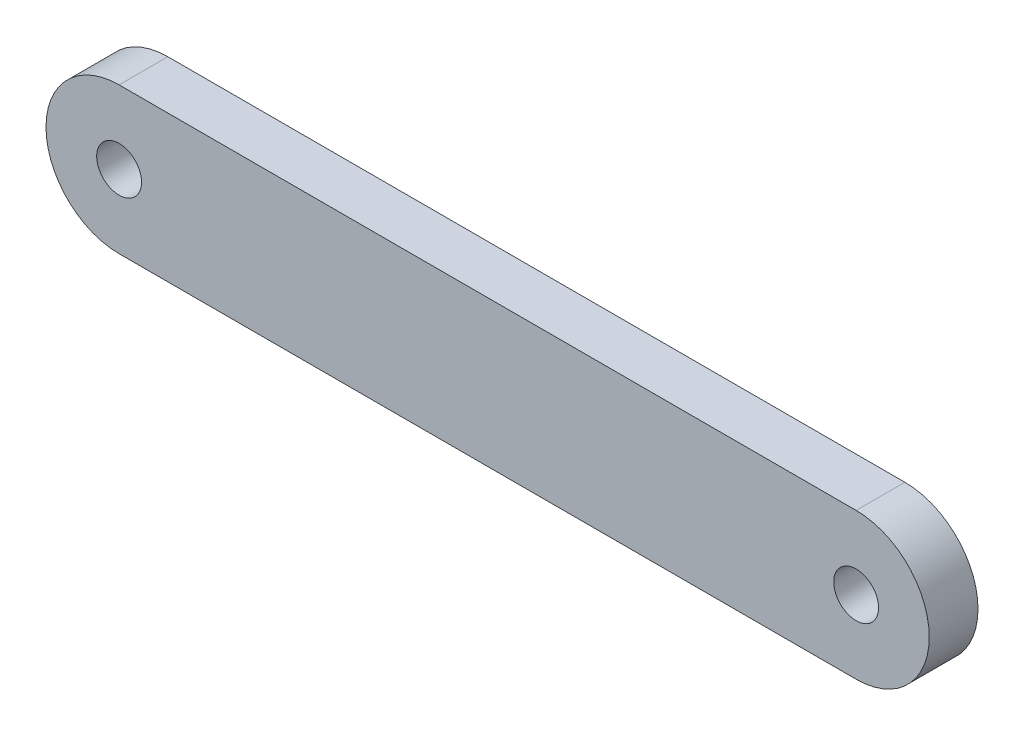
SolidWorks part; units mm, degrees
ref_plane "前视基准面" through (0, 0, 0) normal (0, 0, 1) x (1, 0, 0)
ref_plane "上视基准面" through (0, 0, 0) normal (0, 1, 0) x (1, 0, 0)
ref_plane "右视基准面" through (0, 0, 0) normal (1, 0, 0) x (0, 0, -1)
other "Configuration Table"
sketch "草图1" plane through (0, 0, 0) normal (0, 0, 1) x (1, 0, 0)
  line L1 (-37.8, 7.5) -> (37.8, 7.5)
  line L3 (-37.8, -7.5) -> (37.8, -7.5)
  line L5 (-37.8, 7.5) -> (37.8, -7.5) construction
  line L6 (-37.8, -7.5) -> (37.8, 7.5) construction
  arc A0 (-37.8, 7.5) -> (-37.8, -7.5) centre (-37.8, 0) ccw
  arc A1 (37.8, 7.5) -> (37.8, -7.5) centre (37.8, 0) cw
  circle A2 centre (-37.8, 0) radius 2.3
  circle A3 centre (37.8, 0) radius 2.3
  point P0 (0, 0)
  dimension "D1" = 4.6
  dimension "D2" = 4.6
  dimension "D3" = 75.6
  dimension "D4" = 15
extrude "凸台-拉伸1" add sketch "草图1" along normal blind 5
equation "\"fi\"=4.6"
equation "\"D1@草图1\"=\"fi\""
equation "\"D2@草图1\"=\"fi\""
equation "\"b0\"=75.6"
equation "\"D3@草图1\"=\"b2\""
equation "\"width\"=15"
equation "\"D4@草图1\"=\"width\""
equation "\"depth\"=5"
equation "\"D1@凸台-拉伸1\"=\"depth\""
equation "\"b1\"= \"b0\" *1.4/ 2'rocker"
equation "\"b2\"= \"b0\"'coupler"
equation "\"b3\"= \"b0\" / 2'coupler"
equation "\"b4\"= \"b0\" *2'leg"
equation "\"angle\"= 40*pi/180'ground水平夹角"
